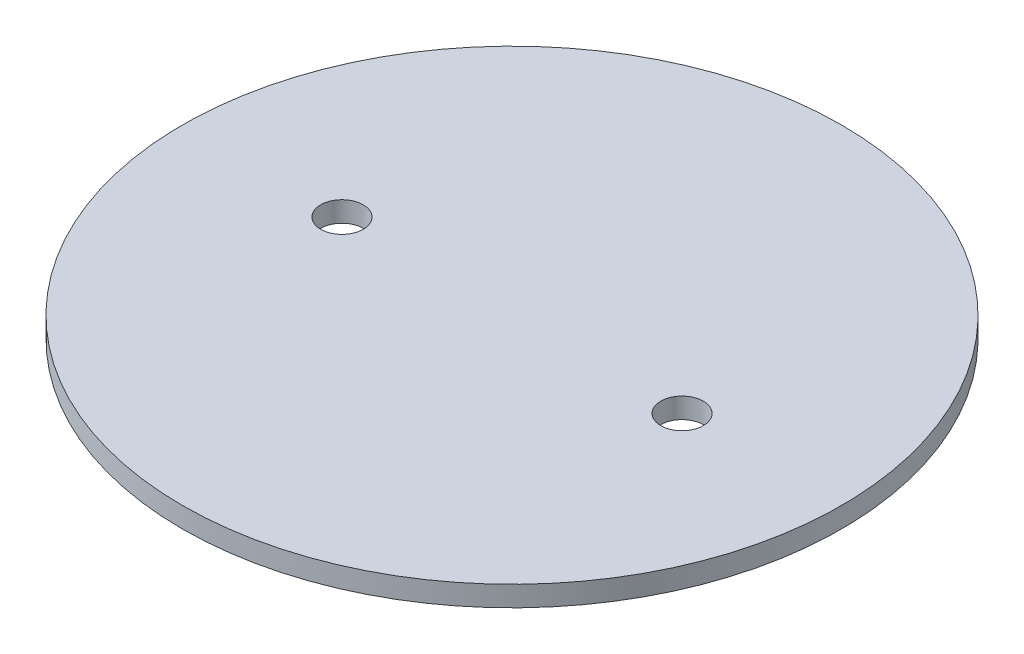
SolidWorks part; units mm, degrees
ref_plane "Front Plane" through (0, 0, 0) normal (0, 0, 1) x (1, 0, 0)
ref_plane "Top Plane" through (0, 0, 0) normal (0, 1, 0) x (1, 0, 0)
ref_plane "Right Plane" through (0, 0, 0) normal (1, 0, 0) x (0, 0, -1)
sketch "Sketch1" plane through (0, 0, 0) normal (0, 1, 0) x (1, 0, 0)
  circle A0 centre (0, 0) radius 96.9
  circle A2 centre (-50, 0) radius 6.25
  circle A3 centre (50, 0) radius 6.25
  point P7 (0, 0)
  dimension "D1" = 193.8
  dimension "D2" = 12.5
  dimension "D3" = 100
  dimension "D4" = 50
extrude "Boss-Extrude1" add sketch "Sketch1" along normal blind 6
